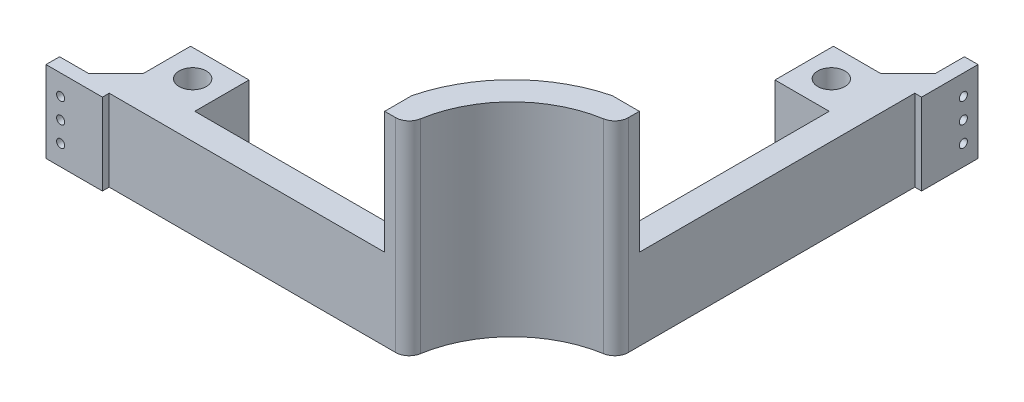
SolidWorks part; units mm, degrees
ref_plane "Front Plane" through (0, 0, 0) normal (0, 0, 1) x (1, 0, 0)
ref_plane "Top Plane" through (0, 0, 0) normal (0, 1, 0) x (1, 0, 0)
ref_plane "Right Plane" through (0, 0, 0) normal (1, 0, 0) x (0, 0, -1)
sketch "Sketch2" plane through (0, 0, 0) normal (0, 1, 0) x (1, 0, 0)
  line L0 (0, 0) -> (0, 41) construction
  line L1 (0, 0) -> (-41, 0) construction
  line L2 (-2.5, 45.3845) -> (-2.5, 49.4444)
  line L3 (-45.3845, 2.5) -> (-49.4444, 2.5)
  line L4 (-2.5, 49.4444) -> (-2.5, 151)
  line L5 (-49.4444, 2.5) -> (-151, 2.5)
  line L21 (0, 0) -> (-64.3582, 64.3582) construction
  line L44 (-129.4444, 12.5) -> (-49.4444, 12.5)
  line L45 (-12.5, 129.4444) -> (-12.5, 49.4444)
  line L46 (-129.4444, 12.5) -> (-129.4444, 32.5)
  line L47 (-129.4444, 32.5) -> (-151, 32.5)
  line L48 (-151, 32.5) -> (-151, 15)
  line L49 (-161, 5) -> (-171.7957, 5)
  line L50 (-171.7957, 5) -> (-171.7957, 0)
  line L51 (-171.7957, 0) -> (-151, 0)
  line L52 (-151, 0) -> (-151, 2.5)
  line L53 (-151, 15) -> (-161, 5)
  line L54 (0, 151) -> (-2.5, 151)
  line L55 (0, 171.7957) -> (0, 151)
  line L56 (-5, 171.7957) -> (0, 171.7957)
  line L57 (-5, 161) -> (-5, 171.7957)
  line L58 (-15, 151) -> (-5, 161)
  line L59 (-32.5, 151) -> (-15, 151)
  line L60 (-32.5, 129.4444) -> (-32.5, 151)
  line L61 (-12.5, 129.4444) -> (-32.5, 129.4444)
  line L62 (-22.5, 129.4444) -> (-22.5, 151) construction
  arc A0 (-6.6848, 40.4514) -> (-40.4514, 6.6848) centre (0, 0) ccw
  arc A1 (-45.3845, 2.5) -> (-40.4514, 6.6848) centre (-45.3845, 7.5) ccw
  arc A2 (-6.6848, 40.4514) -> (-2.5, 45.3845) centre (-7.5, 45.3845) ccw
  arc A5 (-6.6848, 40.4514) -> (-40.4514, 6.6848) centre (0, 0) ccw
  arc A6 (-12.5, 49.4444) -> (-49.4444, 12.5) centre (0, 0) ccw
  circle A7 centre (0, 0) radius 41 construction
  circle A8 centre (-22.5, 140.2222) radius 5
  circle A9 centre (-140.2222, 22.5) radius 5
  point P12 (-2.5, 40.9237)
  point P18 (-151, 5)
  dimension "D1" = 82
  dimension "D2" = 10
  dimension "D5" = 5
  dimension "D6" = 5
  dimension "D7" = 110
  dimension "D3" = 5
  dimension "D4" = 5
  dimension "D8" = 10
  dimension "D9" = 10
  dimension "D11" = 2.5
  dimension "D12" = 5
  dimension "D14" = 110
extrude "Boss-Extrude1" add sketch "Sketch2" along normal blind 30 contours L45 A6 L44 L46 L47 L48 L53 L49 L50 L51 L52 L5 L3 A1 A0 A2 L2 L4 L54 L55 L56 L57 L58 L59 L60 L61
sketch "Sketch10" plane through (-5, 0, 0) normal (-1, 0, 0) x (0, 0, 1)
  line L0 (-166.3979, 30) -> (-166.3979, 0) construction
  line L1 (-161, 30) -> (-171.7957, 30) construction
  line L2 (-161, 0) -> (-171.7957, 0) construction
  line L3 (-171.7957, 15) -> (-161, 15) construction
  line L4 (-171.7957, 30) -> (-171.7957, 0) construction
  line L5 (-161, 30) -> (-161, 0) construction
  line L6 (-171.7957, 22.5) -> (-161, 22.5) construction
  line L7 (-171.7957, 7.5) -> (-161, 7.5) construction
  circle A0 centre (-166.3979, 22.5) radius 1.5
  circle A1 centre (-166.3979, 15) radius 1.5
  circle A2 centre (-166.3979, 7.5) radius 1.5
  dimension "D3" = 3
  dimension "D1" = 7.5
  dimension "D2" = 7.5
extrude "Cut-Extrude1" cut sketch "Sketch10" against normal blind 10
sketch "Sketch11" plane through (0, 0, -5) normal (0, 0, -1) x (-1, 0, 0)
  line L0 (166.3979, 0) -> (166.3979, 30) construction
  line L1 (161, 0) -> (171.7957, 0) construction
  line L2 (161, 30) -> (171.7957, 30) construction
  line L3 (171.7957, 15) -> (161, 15) construction
  line L4 (171.7957, 30) -> (171.7957, 0) construction
  line L5 (161, 30) -> (161, 0) construction
  line L6 (171.7957, 7.5) -> (161, 7.5) construction
  line L7 (171.7957, 22.5) -> (161, 22.5) construction
  circle A0 centre (166.3979, 22.5) radius 1.5
  circle A1 centre (166.3979, 15) radius 1.5
  circle A2 centre (166.3979, 7.5) radius 1.5
  dimension "D3" = 3
  dimension "D1" = 7.5
  dimension "D2" = 7.5
extrude "Cut-Extrude3" cut sketch "Sketch11" against normal blind 10
sketch "Sketch13" plane through (0, 30, 0) normal (0, 1, 0) x (1, 0, 0)
  line L0 (-49.4444, 12.5) -> (-49.4444, 2.5)
  line L1 (-45.3845, 2.5) -> (-151, 2.5) construction
  line L2 (-12.5, 49.4444) -> (-2.5, 49.4444)
  line L3 (-2.5, 45.3845) -> (-2.5, 151) construction
  line L4 (-45.3845, 2.5) -> (-49.4444, 2.5)
  line L5 (-2.5, 45.3845) -> (-2.5, 49.4444)
  arc A0 (-45.3845, 2.5) -> (-40.4514, 6.6848) centre (-45.3845, 7.5) ccw construction
  arc A1 (-6.6848, 40.4514) -> (-2.5, 45.3845) centre (-7.5, 45.3845) ccw construction
  arc A2 (-6.6848, 40.4514) -> (-40.4514, 6.6848) centre (0, 0) ccw construction
  arc A3 (-12.5, 49.4444) -> (-49.4444, 12.5) centre (0, 0) ccw construction
  arc A4 (-45.3845, 2.5) -> (-40.4514, 6.6848) centre (-45.3845, 7.5) ccw
  arc A5 (-6.6848, 40.4514) -> (-2.5, 45.3845) centre (-7.5, 45.3845) ccw
  arc A6 (-6.6848, 40.4514) -> (-40.4514, 6.6848) centre (0, 0) ccw
  arc A7 (-12.5, 49.4444) -> (-49.4444, 12.5) centre (0, 0) ccw
extrude "Boss-Extrude2" add sketch "Sketch13" along normal blind 45 contours L5 L2 A7 L0 L4 A4 A6 A5
